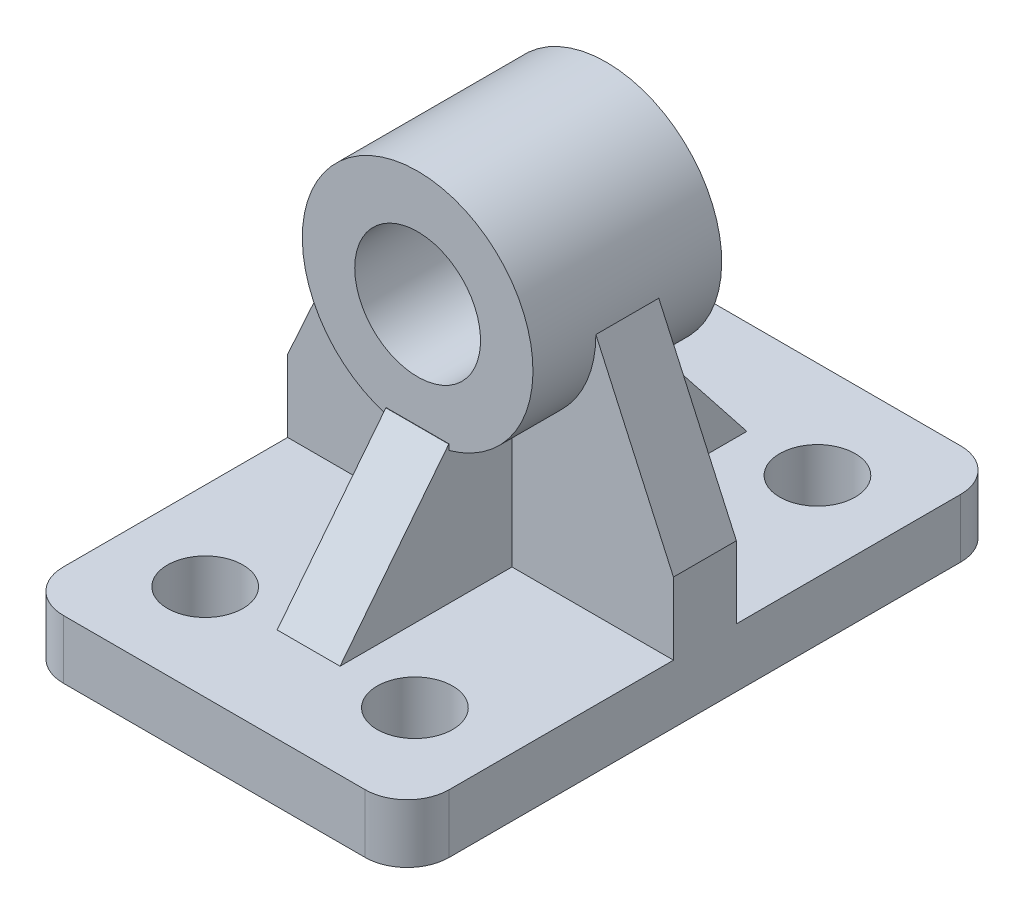
SolidWorks part; units mm, degrees
ref_plane "Front Plane" through (0, 0, 0) normal (0, 0, 1) x (1, 0, 0)
ref_plane "Top Plane" through (0, 0, 0) normal (0, 1, 0) x (1, 0, 0)
ref_plane "Right Plane" through (0, 0, 0) normal (1, 0, 0) x (0, 0, -1)
sketch "Sketch1" plane through (0, 0, 0) normal (0, 1, 0) x (1, 0, 0)
  line L0 (153.8012, 0) -> (225.8012, 0)
  line L9 (235.8012, 10) -> (235.8012, 132)
  line L10 (225.8012, 142) -> (153.8012, 142)
  line L11 (143.8012, 132) -> (143.8012, 10)
  arc A8 (143.8012, 132) -> (153.8012, 142) centre (153.8012, 132) cw
  arc A9 (225.8012, 142) -> (235.8012, 132) centre (225.8012, 132) cw
  arc A10 (235.8012, 10) -> (225.8012, 0) centre (225.8012, 10) cw
  arc A11 (153.8012, 0) -> (143.8012, 10) centre (153.8012, 10) cw
  circle A12 centre (164.8012, 22.845) radius 9
  circle A13 centre (214.8012, 22.845) radius 9
  circle A14 centre (214.8012, 118.8297) radius 9
  circle A15 centre (164.8012, 118.8297) radius 9
  point P8 (235.8012, 142)
  point P11 (235.8012, 0)
  dimension "D2" = 10
  dimension "D1" = 142
  dimension "D4" = 21
  dimension "D3" = 21
  dimension "D5" = 21
  dimension "D6" = 50
  dimension "D7" = 21
  dimension "D8" = 50
extrude "Boss-Extrude1" add sketch "Sketch1" against normal blind 14
ref_plane "Plane1" through (0, 0, -71) normal (0, 0, 1) x (1, 0, 0)
sketch "Sketch2" plane through (0, 0, -71) normal (0, 0, 1) x (1, 0, 0)
  line L0 (153.8012, 0) -> (225.8012, 0) construction
  circle A0 centre (189.8012, 58) radius 27.5
  circle A1 centre (189.8012, 58) radius 15
  dimension "D1" = 55
  dimension "D2" = 58
extrude "Boss-Extrude2" add sketch "Sketch2" along normal blind 22.5 separate body
sketch "Sketch3" plane through (0, 0, -71) normal (0, 0, -1) x (-1, 0, 0)
  circle A0 centre (-189.8012, 58) radius 15
  circle A1 centre (-189.8012, 58) radius 27.5
extrude "Boss-Extrude3" add sketch "Sketch3" along normal blind 22.5
sketch "Sketch4" plane through (0, 0, -71) normal (0, 0, 1) x (1, 0, 0)
  line L0 (235.8012, 0) -> (235.8012, 17.1645)
  line L1 (143.8012, 17.1645) -> (162.3012, 58)
  line L2 (143.8012, 0) -> (143.8012, 17.1645)
  line L3 (235.8012, 17.1645) -> (217.3012, 58)
  line L4 (143.8012, 0) -> (235.8012, 0)
  circle A1 centre (189.8012, 58) radius 27.5 construction
  circle A2 centre (189.8012, 58) radius 27.5
extrude "Boss-Extrude4" add sketch "Sketch4" along normal mid plane 15 contours A2 L1 L2 L4 L0 L3
ref_plane "Plane5" through (189.8012, 0, 0) normal (-1, 0, 0) x (0, 0, 1)
sketch "Sketch6" plane through (189.8012, 0, 0) normal (-1, 0, 0) x (0, 0, 1)
  line L1 (-132, 0) -> (-78.5, 0) construction
  line L2 (-119.5, 0) -> (-78.5, 0)
  line L5 (-63.5, 0) -> (-63.5, 30.5)
  line L9 (-63.5, 0) -> (-10, 0) construction
  line L10 (-22.5, 0) -> (-63.5, 0)
  line L11 (-119.5, 0) -> (-93.5, 32.9051)
  line L12 (-65.3951, 32.9051) -> (-65.3951, 0)
  line L13 (-76.5069, 0) -> (-76.5069, 30.5)
  line L14 (-78.5, 0) -> (-76.5069, 0)
  line L17 (-65.3951, 30.5) -> (-63.5, 30.5)
  line L18 (-65.3951, 0) -> (-63.5, 0)
  line L19 (-93.5, 32.9051) -> (-76.5069, 32.9051)
  line L20 (-93.5, 85.5) -> (-93.5, 30.5) construction
  line L21 (-76.5069, 32.9051) -> (-76.5069, 30.5)
  line L22 (-65.3951, 32.9051) -> (-48.4242, 32.9051)
  line L23 (-48.4242, 32.9051) -> (-22.5, 0)
  dimension "D1" = 41
  dimension "D2" = 41
extrude "Boss-Extrude9" add sketch "Sketch6" along normal mid plane 15 contours L19 L21 L13 L14 L2 L11 | L18 L12 L22 L23 L10
